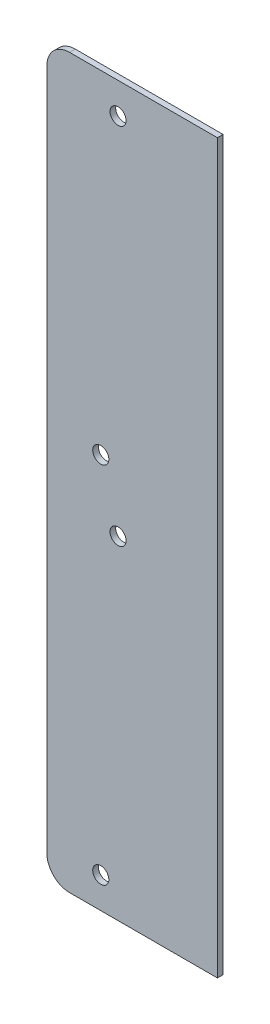
SolidWorks part; units mm, degrees
material "ASTM A36 Steel"
ref_plane "X-Y Datum" through (0, 0, 0) normal (0, 0, 1) x (1, 0, 0)
ref_plane "X-Z Datum" through (0, 0, 0) normal (0, 1, 0) x (1, 0, 0)
ref_plane "Y-Z Datum" through (0, 0, 0) normal (1, 0, 0) x (0, 0, -1)
sketch "Sketch1" plane through (0, 0, 0) normal (0, 0, 1) x (1, 0, 0)
  line L0 (-2.413, -42.164) -> (2.413, -42.164) construction
  line L1 (-17.4625, 50.8) -> (17.4625, 50.8)
  line L2 (-17.4625, 50.8) -> (-17.4625, -50.8)
  line L3 (-17.4625, -50.8) -> (17.4625, -50.8)
  line L4 (17.4625, 50.8) -> (17.4625, -50.8)
  line L5 (-17.4625, 50.8) -> (17.4625, -50.8) construction
  line L6 (-17.4625, -50.8) -> (17.4625, 50.8) construction
  line L7 (2.413, -42.164) -> (2.413, 42.164) construction
  point P0 (0, 0)
  point P6 (2.413, 42.164)
  point P7 (-2.413, -42.164)
  point P10 (2.413, 0)
  point P12 (0, 0)
  point P13 (0, 0)
  point P16 (0, -42.164)
  dimension "D1" = 34.925
  dimension "D2" = 101.6
  dimension "D3" = 84.328
  dimension "D4" = 4.826
extrude "Boss-Extrude1" add sketch "Sketch1" along normal blind 1.5875
hole_wizard "M4 Clearance Hole1" positions "Sketch3" profile "Sketch4" hole size "M4" standard "ANSI Metric" end condition through all
sketch "Sketch3" plane through (0, 0, 1.5875) normal (0, 0, 1) x (1, 0, 0)
  point P0 (-2.413, -42.164)
  point P3 (2.413, 42.164)
sketch "Sketch4" plane through (-2.413, -42.164, 1.5875) normal (1, 0, 0) x (0, -1, 0)
  line L0 (0, 0) -> (0, 1.5875)
  line L1 (0, 1.5875) -> (2.25, 1.5875)
  line L2 (2.25, 1.5875) -> (2.25, 0)
  line L5 (2.25, 0) -> (0, 0)
  line L11 (0, -6.35) -> (0, 107.95) construction
  dimension "Thru Hole Dia." = 4.5
  dimension "Thru Hole Depth" = 1.5875
sketch "Sketch8" plane through (0, 0, 1.5875) normal (0, 0, 1) x (1, 0, 0)
  line L1 (-17.4625, 50.8) -> (17.4625, 50.8)
  line L2 (-17.4625, 50.8) -> (-17.4625, 152.4)
  line L3 (-17.4625, 152.4) -> (17.4625, 152.4)
  line L4 (17.4625, 50.8) -> (-17.4625, 50.8)
  line L5 (17.4625, -50.8) -> (17.4625, 50.8)
  line L6 (-17.4625, -50.8) -> (17.4625, -50.8)
  line L7 (-17.4625, 50.8) -> (-17.4625, -50.8)
  line L8 (17.4625, 50.8) -> (-17.4625, 50.8)
  line L9 (17.4625, -50.8) -> (17.4625, 50.8)
  line L10 (-17.4625, -50.8) -> (17.4625, -50.8)
  line L11 (-17.4625, 50.8) -> (-17.4625, -50.8)
  line L12 (17.4625, 50.8) -> (17.4625, 152.4)
  circle A0 centre (-2.413, -42.164) radius 2.25 construction
  circle A1 centre (2.413, 42.164) radius 2.25 construction
  circle A2 centre (-2.413, -42.164) radius 2.25
  circle A3 centre (2.413, 42.164) radius 2.25
  circle A6 centre (2.413, 143.764) radius 2.25
  circle A7 centre (-2.413, 59.436) radius 2.25
  dimension "D2" = 101.6
  dimension "D1" = 0
extrude "Boss-Extrude4" add sketch "Sketch8" against normal blind 1.5875
sketch "Sketch6" plane through (0, 0, 1.5875) normal (0, 0, 1) x (1, 0, 0)
  line L0 (17.4625, -50.8) -> (17.4625, 152.4) construction
  line L1 (-17.4625, -50.8) -> (17.4625, -50.8)
  line L2 (-17.4625, -50.8) -> (-17.4625, -66.675)
  line L3 (-17.4625, -66.675) -> (17.4625, -66.675)
  line L4 (17.4625, -50.8) -> (17.4625, -66.675)
  dimension "D1" = 15.875
extrude "Boss-Extrude3" [suppressed] add sketch "Sketch6" against normal blind 3.175
sketch "Sketch9" plane through (0, 0, 1.5875) normal (0, 0, 1) x (1, 0, 0)
  line L0 (-17.4625, -50.8) -> (17.4625, -50.8) construction
  line L1 (17.4625, 152.4) -> (30.1625, 152.4)
  line L2 (17.4625, 152.4) -> (17.4625, -50.8)
  line L3 (17.4625, -50.8) -> (30.1625, -50.8)
  line L4 (30.1625, 152.4) -> (30.1625, -50.8)
  dimension "D1" = 12.7
extrude "Boss-Extrude5" add sketch "Sketch9" against normal blind 1.5875
fillet "Fillet1" radius 6.35 2 edges at (-17.4625, -50.8, 0.7937) (-17.4625, 152.4, 0.7937)
